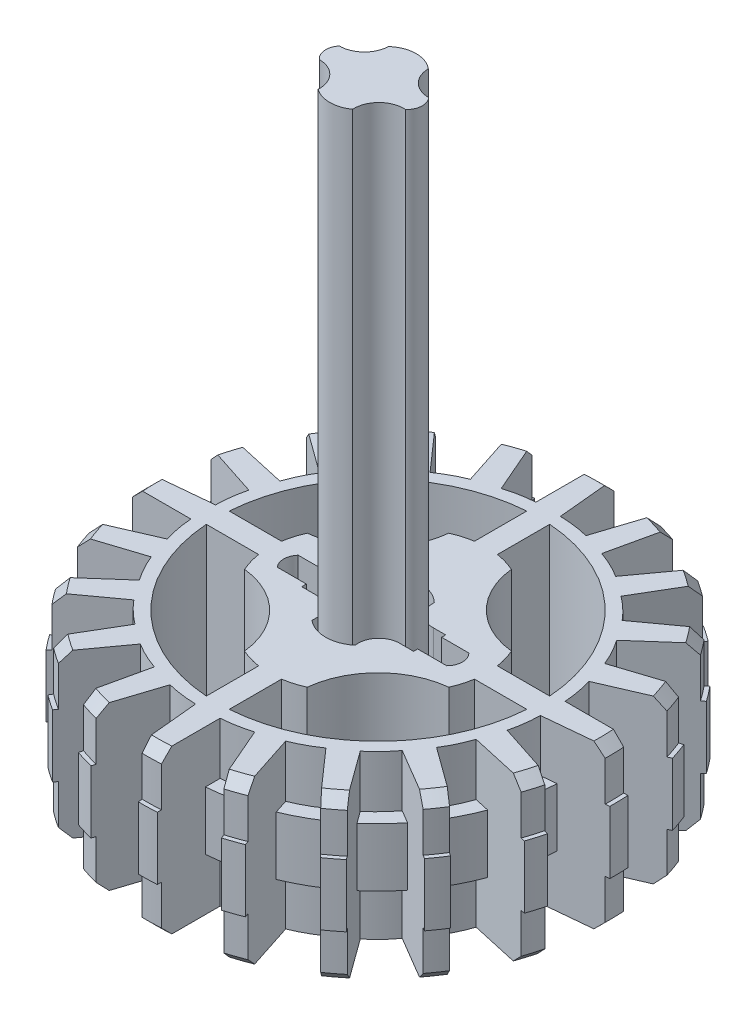
SolidWorks part; units mm, degrees
ref_plane "Front Plane" through (0, 0, 0) normal (0, 0, 1) x (1, 0, 0)
ref_plane "Top Plane" through (0, 0, 0) normal (0, 1, 0) x (1, 0, 0)
ref_plane "Right Plane" through (0, 0, 0) normal (1, 0, 0) x (0, 0, -1)
sketch "Sketch1" plane through (0, 0, 0) normal (1, 0, 0) x (0, 0, -1)
  line L0 (0, 3.9) -> (0, -3.9)
  line L8 (-7.7, 5.6133) -> (-7.7, -5.5023) construction
  line L9 (0, 3.9) -> (2.9054, 3.9)
  line L10 (3.4, 3.4054) -> (3.4, 1.5)
  line L11 (2.9054, -3.9) -> (0, -3.9)
  line L12 (2.9054, 3.9) -> (3.4, 3.4054)
  line L13 (2.9054, -3.9) -> (3.4, -3.4054)
  line L14 (3.6, 1.5) -> (3.6, -1.5)
  line L15 (3.6, 1.5) -> (3.4, 1.5)
  line L16 (3.6, -1.5) -> (3.4, -1.5)
  line L17 (3.4, -1.5) -> (3.4, -3.4054)
  point P2 (0, 0)
  point P10 (3.6, 0)
  dimension "D1" = 7.8
  dimension "D2" = 3.4
  dimension "D3" = 135
  dimension "D4" = 0.4946
  dimension "D5" = 7.7
  dimension "D6" = 3
  dimension "D7" = 0.2
revolve "Revolve2" add sketch "Sketch1" angle 360 about L8
sketch "Sketch2" plane through (0, 3.9, 0) normal (0, 1, 0) x (1, 0, 0)
  line L0 (0.7, -15.9681) -> (0.7, -19.9681)
  line L1 (2.1, -15.7081) -> (3.7, -19.4011)
  line L2 (0, -55) -> (0, 55) construction
  arc A1 (0.7, -15.9681) -> (2.1, -15.7081) centre (0.2714, -9.7611) ccw
  arc A2 (0.7, -19.9681) -> (3.7, -19.4011) centre (0.0281, -8.1932) ccw
  circle A4 centre (0, -7.7) radius 11.3 construction
  circle A5 centre (0, -7.7) radius 7.7 construction
  point P2 (2.1, -15.1081)
  point P18 (0.7, -15.3681)
  dimension "D4" = 4
  dimension "D1" = 0.6
  dimension "D2" = 3
  dimension "D3" = 0.6
  dimension "D5" = 1.4
  dimension "D6" = 0.7
extrude "Cut-Extrude1" cut sketch "Sketch2" against normal blind 10
pattern_circular "CirPattern1" count 20 over 360 about axis through (0, 0, 7.7) along (0, 1, 0) of "Cut-Extrude1"
sketch "Sketch3" plane through (0, 0, 0) normal (1, 0, 0) x (0, 0, -1)
  line L6 (0, 1.4) -> (0, -1.4)
  line L7 (1.3, -1.4) -> (1.3, 1.4)
  line L8 (1.3, 1.4) -> (0, 1.4)
  line L9 (0, -1.4) -> (1.3, -1.4)
  line L10 (-7.7, 4.9195) -> (-7.7, -5.3783) construction
  point P2 (0, 0)
  dimension "D1" = 2.8
  dimension "D2" = 1.3
  dimension "D3" = 7.7
revolve "Revolve3" add sketch "Sketch3" angle 360 about L10
sketch "Sketch4" plane through (0, 0, 0) normal (0, 1, 0) x (1, 0, 0)
  line L0 (-0.55, -15.3803) -> (-0.55, -12.8731)
  line L2 (0.55, -12.8731) -> (0.55, -15.3803)
  line L3 (0, -4.29) -> (0, 4.29) construction
  line L7 (-0.55, -0.0197) -> (-0.55, -2.5269)
  line L8 (0.55, -2.5269) -> (0.55, -0.0197)
  line L10 (7.6803, -8.25) -> (5.1731, -8.25)
  line L11 (5.1731, -7.15) -> (7.6803, -7.15)
  line L13 (0.55, -0.0197) -> (0.55, -2.5269)
  line L14 (-0.55, -2.5269) -> (-0.55, -0.0197)
  line L16 (-7.6803, -7.15) -> (-5.1731, -7.15)
  line L17 (-5.1731, -8.25) -> (-7.6803, -8.25)
  circle A0 centre (0, -7.7) radius 7.7 construction
  arc A1 (-0.55, -15.3803) -> (0.55, -15.3803) centre (0, -7.7) ccw
  arc A2 (-1.5, -12.5941) -> (-0.55, -12.8731) centre (0, -9.2433) ccw
  arc A3 (-1.5, -12.5941) -> (-4.8941, -9.2) centre (-5.2915, -12.9915) ccw
  arc A4 (1.5, -12.5941) -> (4.8941, -9.2) centre (5.2915, -12.9915) cw
  arc A7 (0.55, -12.8731) -> (1.5, -12.5941) centre (0, -9.2433) ccw
  arc A8 (-1.5, -2.8059) -> (-0.55, -2.5269) centre (0, -6.1567) cw
  arc A9 (0.55, -2.5269) -> (1.5, -2.8059) centre (0, -6.1567) cw
  arc A10 (-1.5, -2.8059) -> (-4.8941, -6.2) centre (-5.2915, -2.4085) cw
  arc A13 (1.5, -2.8059) -> (4.8941, -6.2) centre (5.2915, -2.4085) ccw
  arc A14 (4.8941, -9.2) -> (5.1731, -8.25) centre (1.5433, -7.7) ccw
  arc A15 (5.1731, -7.15) -> (4.8941, -6.2) centre (1.5433, -7.7) ccw
  arc A16 (1.5, -2.8059) -> (0.55, -2.5269) centre (0, -6.1567) ccw
  arc A17 (-0.55, -2.5269) -> (-1.5, -2.8059) centre (0, -6.1567) ccw
  arc A18 (-4.8941, -6.2) -> (-5.1731, -7.15) centre (-1.5433, -7.7) ccw
  arc A19 (-5.1731, -8.25) -> (-4.8941, -9.2) centre (-1.5433, -7.7) ccw
  arc A20 (-7.6803, -7.15) -> (-7.6803, -8.25) centre (0, -7.7) ccw
  arc A21 (7.6803, -7.15) -> (7.6803, -8.25) centre (0, -7.7) cw
  arc A22 (-0.55, -0.0197) -> (0.55, -0.0197) centre (0, -7.7) cw
  arc A23 (-0.55, -0.0197) -> (0.55, -0.0197) centre (0, -7.7) cw
  point P7 (0, -15.4)
  point P74 (0, -7.7)
  dimension "D1" = 1.1
  dimension "D2" = 1.1
  dimension "D3" = 2.5072
  dimension "D4" = 2.5072
extrude "Boss-Extrude1" add sketch "Sketch4" along normal mid plane 7.8 contours A22 L7 A8 A10 A18 L16 A20 L17 A19 A3 A2 L0 A1 L2 A7 A4 A14 L10 A21 L11 A15 A13 A9 L8
sketch "Sketch6" plane through (0, 3.9, 0) normal (0, 1, 0) x (1, 0, 0)
  line L0 (-4.1964, -7.3294) -> (-2.8925, -7.3294)
  line L1 (-2.8925, -7.3294) -> (-2.8925, -7.106)
  line L2 (-2.8925, -7.106) -> (-2.3013, -7.106)
  line L3 (-4.1964, -8.3294) -> (-2.8029, -8.3294)
  line L4 (-2.8029, -8.3294) -> (-2.8029, -8.5528)
  line L5 (-2.8029, -8.5528) -> (-2.2118, -8.5528)
  line L6 (-0.1124, -5.5794) -> (-0.1305, -10.0793) construction
  line L8 (2.5617, -8.3596) -> (2.5617, -8.5541)
  line L9 (2.5617, -8.5541) -> (1.9706, -8.5541)
  line L10 (2.65, -7.1046) -> (2.0588, -7.1046)
  line L11 (2.65, -7.2991) -> (2.65, -7.1046)
  line L12 (3.9545, -8.3596) -> (2.5617, -8.3596)
  line L13 (3.9545, -7.2991) -> (2.65, -7.2991)
  arc A0 (-4.1964, -7.3294) -> (-4.1964, -8.3294) centre (-3.6375, -7.8294) ccw
  arc A1 (-2.2118, -8.5528) -> (-1.1679, -9.7021) centre (-2.1543, -9.5492) cw
  arc A2 (-1.1679, -9.7021) -> (0.9069, -9.7021) centre (-0.1305, -8.4643) ccw
  arc A3 (0.9069, -9.7021) -> (1.9706, -8.5541) centre (1.8932, -9.5492) cw
  arc A4 (1.0359, -6.0359) -> (2.0588, -7.1046) centre (2.0315, -6.1069) ccw
  arc A5 (-1.2473, -6.0683) -> (1.0359, -6.0359) centre (-0.0895, -7.1942) cw
  arc A6 (-2.3013, -7.106) -> (-1.2473, -6.0683) centre (-2.2446, -6.1095) ccw
  arc A7 (3.9545, -7.2991) -> (3.9545, -8.3596) centre (3.4243, -7.8294) cw
  point P14 (-0.1215, -7.8294)
  point P16 (-4.3874, -7.8294)
  point P17 (4.1742, -7.8294)
  point P25 (-0.1124, -5.5794)
  point P26 (-0.1305, -10.0793)
  dimension "D1" = 4.5
  dimension "D2" = 1
extrude "Cut-Extrude3" cut sketch "Sketch6" against normal blind 7.8
sketch "Sketch7" plane through (0, 0, 0) normal (0, 1, 0) x (1, 0, 0)
  line L32 (-4.3874, -7.8294) -> (-4.1874, -7.8294) construction
  line L51 (-0.1124, -5.5794) -> (-0.1305, -10.0793) construction
  line L81 (2.65, -7.1046) -> (2.65, -7.2991)
  line L98 (-2.8029, -8.3294) -> (-4.1964, -8.3294) construction
  line L99 (-2.8029, -8.5528) -> (-2.8029, -8.3294) construction
  line L100 (-2.1568, -8.5511) -> (-2.8029, -8.5528) construction
  line L101 (3.9545, -8.3596) -> (2.5617, -8.3596) construction
  line L102 (2.5617, -8.5541) -> (1.9706, -8.5541) construction
  line L103 (2.65, -7.2991) -> (3.9545, -7.2991) construction
  line L104 (2.0321, -7.105) -> (2.65, -7.1046) construction
  line L105 (-2.8925, -7.106) -> (-2.2471, -7.1076) construction
  line L106 (-4.1964, -7.3294) -> (-2.8925, -7.3294) construction
  line L107 (-2.8925, -7.3294) -> (-2.8925, -7.106) construction
  line L108 (-2.6925, -7.3065) -> (-2.2476, -7.3076) construction
  line L109 (-2.42, -7.8294) -> (2.2229, -7.8294) construction
  line L110 (-2.1573, -8.3511) -> (-2.6029, -8.3522) construction
  line L111 (-2.6029, -8.1294) -> (-4.0984, -8.1294) construction
  line L112 (-4.0984, -7.5294) -> (-2.6925, -7.5294) construction
  line L113 (-2.6925, -7.5294) -> (-2.6925, -7.3065) construction
  line L114 (-2.6029, -8.3522) -> (-2.6029, -8.1294) construction
  line L115 (2.0322, -7.305) -> (2.45, -7.3047) construction
  line L117 (2.3617, -8.3541) -> (1.978, -8.3541) construction
  line L118 (2.5617, -8.3596) -> (2.5617, -8.5541) construction
  line L119 (3.864, -8.1596) -> (2.3617, -8.1596) construction
  line L120 (2.45, -7.4991) -> (3.864, -7.4991) construction
  line L121 (2.45, -7.3047) -> (2.45, -7.4991) construction
  line L122 (2.3617, -8.1596) -> (2.3617, -8.3541) construction
  arc A32 (-4.1964, -7.3294) -> (-4.1964, -8.3294) centre (-3.6375, -7.8294) ccw construction
  arc A34 (1.0359, -6.0359) -> (-1.2473, -6.0683) centre (-0.0895, -7.1942) ccw construction
  arc A35 (-1.1679, -9.7021) -> (0.9069, -9.7021) centre (-0.1305, -8.4643) ccw construction
  arc A64 (1.978, -8.3541) -> (0.6968, -9.6123) centre (1.8932, -9.5492) ccw
  arc A65 (0.6968, -9.6123) -> (-0.9578, -9.6123) centre (-0.1305, -8.4643) cw
  arc A66 (-2.1573, -8.3511) -> (-0.9578, -9.6123) centre (-2.1543, -9.5492) cw
  arc A68 (-2.2476, -7.3076) -> (-1.0473, -6.1526) centre (-2.2446, -6.1095) ccw
  arc A69 (-1.0473, -6.1526) -> (0.8335, -6.1217) centre (-0.0895, -7.1942) cw
  arc A70 (0.8335, -6.1217) -> (2.0322, -7.305) centre (2.0315, -6.1069) ccw
  arc A72 (-4.1964, -7.3294) -> (-4.1964, -8.3294) centre (-3.6375, -7.8294) ccw construction
  arc A73 (-2.1568, -8.5511) -> (-1.1679, -9.7021) centre (-2.1543, -9.5492) cw construction
  arc A74 (0.9069, -9.7021) -> (-1.1679, -9.7021) centre (-0.1305, -8.4643) cw construction
  arc A75 (1.9706, -8.5541) -> (0.9069, -9.7021) centre (1.8932, -9.5492) ccw construction
  arc A76 (3.9545, -7.2991) -> (3.9545, -8.3596) centre (3.4243, -7.8294) cw construction
  arc A77 (1.0359, -6.0359) -> (2.0321, -7.105) centre (2.0315, -6.1069) ccw construction
  arc A78 (-1.2473, -6.0683) -> (1.0359, -6.0359) centre (-0.0895, -7.1942) cw construction
  arc A79 (-2.2471, -7.1076) -> (-1.2473, -6.0683) centre (-2.2446, -6.1095) ccw construction
  arc A80 (-2.2476, -7.3076) -> (-2.1573, -8.3511) centre (-1.6807, -7.7842) ccw
  arc A81 (2.0322, -7.305) -> (1.978, -8.3541) centre (1.4806, -7.8024) cw
  arc A82 (-4.0984, -7.5294) -> (-4.0984, -8.1294) centre (-3.6375, -7.8294) ccw construction
  arc A83 (3.864, -7.4991) -> (3.864, -8.1596) centre (3.4243, -7.8294) cw construction
  dimension "D1" = 0.2
extrude "Boss-Extrude2" add sketch "Sketch7" along normal blind 26 separate body contours A81 A70 A69 A68 A80 A66 A65 A64
